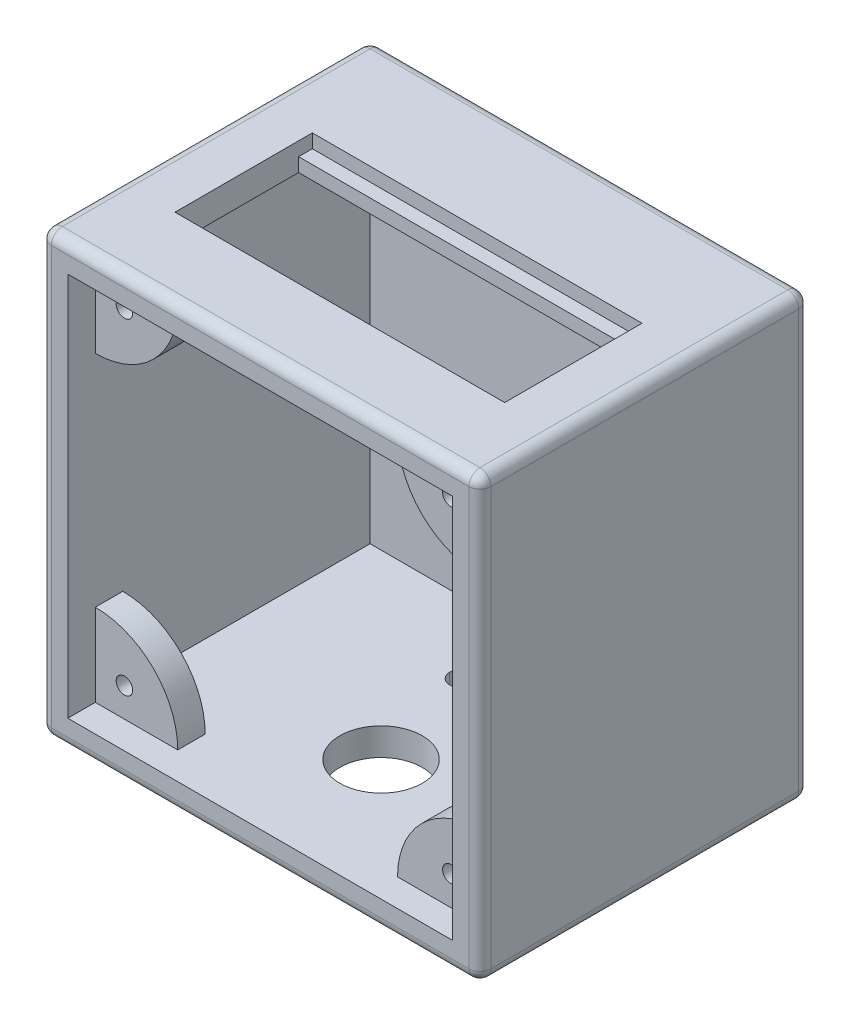
SolidWorks part; units mm, degrees
ref_plane "Спереди" through (0, 0, 0) normal (0, 0, 1) x (1, 0, 0)
ref_plane "Сверху" through (0, 0, 0) normal (0, 1, 0) x (1, 0, 0)
ref_plane "Справа" through (0, 0, 0) normal (1, 0, 0) x (0, 0, -1)
other "Configuration Table"
sketch "Эскиз1" plane through (0, 0, 0) normal (0, 0, 1) x (1, 0, 0)
  line L1 (40, -40) -> (-40, -40)
  line L2 (40, -40) -> (40, 40)
  line L3 (40, 40) -> (-40, 40)
  line L4 (-40, -40) -> (-40, 40)
  line L5 (40, -40) -> (-40, 40) construction
  line L6 (40, 40) -> (-40, -40) construction
  line L11 (35, -35) -> (-35, 35) construction
  line L12 (35, 35) -> (-35, -35) construction
  point P0 (0, 0)
  point P6 (0, 0)
  dimension "D1" = 80
  dimension "D2" = 80
extrude "Бобышка-Вытянуть2" add sketch "Эскиз1" along normal blind 60
sketch "Эскиз2" plane through (0, 0, 60) normal (0, 0, 1) x (1, 0, 0)
  line L0 (-40, 40) -> (-40, -40) construction
  line L1 (35, -35) -> (-35, -35)
  line L2 (35, -35) -> (35, 35)
  line L3 (35, 35) -> (-35, 35)
  line L4 (-35, -35) -> (-35, 35)
  line L5 (35, -35) -> (-35, 35) construction
  line L6 (35, 35) -> (-35, -35) construction
  line L7 (-40, -40) -> (40, -40) construction
  point P0 (0, 0)
  dimension "D1" = 5
  dimension "D2" = 5
extrude "Вырез-Вытянуть1" cut sketch "Эскиз2" against normal blind 55
sketch "Эскиз3" plane through (0, 0, 60) normal (0, 0, 1) x (1, 0, 0)
  line L0 (-35, 35) -> (-35, -35) construction
  line L3 (35, 35) -> (-35, 35) construction
  line L4 (-35, 35) -> (-35, -35) construction
  line L5 (-35, -35) -> (35, -35) construction
  line L6 (-35, -35) -> (35, -35) construction
  line L7 (35, -35) -> (35, 35) construction
  line L8 (-35, 35) -> (-35, 20)
  line L9 (-20, 35) -> (-35, 35)
  line L10 (35, 35) -> (35, 20)
  line L11 (20, 35) -> (35, 35)
  line L12 (20, -35) -> (35, -35)
  line L13 (35, -35) -> (35, -20)
  line L14 (-35, -20) -> (-35, -35)
  line L15 (-35, -35) -> (-20, -35)
  arc A0 (-35, 20) -> (-20, 35) centre (-35, 35) ccw
  arc A1 (20, 35) -> (35, 20) centre (35, 35) ccw
  arc A2 (-35, -20) -> (-20, -35) centre (-35, -35) cw
  arc A3 (20, -35) -> (35, -20) centre (35, -35) cw
  dimension "D1" = 15
  dimension "D2" = 15
  dimension "D3" = 15
  dimension "D4" = 15
extrude "Бобышка-Вытянуть3" add sketch "Эскиз3" against normal blind 10 separate body contours L13 A3 L12 | L9 L8 A0 | L11 L10 A1 | L15 A2 L14
sketch "Эскиз5" plane through (0, 0, 60) normal (0, 0, 1) x (1, 0, 0)
  line L0 (-35, 35) -> (-20, 35)
  line L1 (-35, 20) -> (-35, 35)
  line L2 (35, 35) -> (35, 20)
  line L3 (20, 35) -> (35, 35)
  line L4 (35, -20) -> (35, -35)
  line L5 (35, -35) -> (20, -35)
  line L6 (-20, -35) -> (-35, -35)
  line L7 (-35, -35) -> (-35, -20)
  arc A0 (-35, 20) -> (-20, 35) centre (-35, 35) ccw
  arc A1 (20, 35) -> (35, 20) centre (35, 35) ccw
  arc A2 (35, -20) -> (20, -35) centre (35, -35) ccw
  arc A3 (-20, -35) -> (-35, -20) centre (-35, -35) ccw
extrude "Вырез-Вытянуть2" cut sketch "Эскиз5" against normal blind 5
sketch "Эскиз6" plane through (0, 0, 55) normal (0, 0, 1) x (1, 0, 0)
  line L0 (-35, 35) -> (-24.3934, 24.3934) construction
  line L1 (35, 35) -> (24.3934, 24.3934) construction
  line L3 (-40, 0) -> (40, 0) construction
  line L4 (-40, 40) -> (-40, -40) construction
  line L5 (40, -40) -> (40, 40) construction
  arc A0 (-35, 20) -> (-20, 35) centre (-35, 35) ccw construction
  circle A1 centre (-29.6967, 29.6967) radius 1.5
  arc A2 (20, 35) -> (35, 20) centre (35, 35) ccw construction
  circle A3 centre (29.6967, 29.6967) radius 1.5
  circle A4 centre (29.6967, -29.6967) radius 1.5
  circle A5 centre (-29.6967, -29.6967) radius 1.5
  dimension "D1" = 3
  dimension "D2" = 3
extrude "Вырез-Вытянуть3" cut sketch "Эскиз6" against normal blind 5
sketch "Эскиз7" plane through (0, -40, 0) normal (0, -1, 0) x (1, 0, 0)
  line L0 (0, 60) -> (0, 0) construction
  line L1 (-40, 60) -> (40, 60) construction
  line L2 (-40, 0) -> (40, 0) construction
  line L3 (-40, 60) -> (-40, 0) construction
  line L4 (40, 5) -> (-40, 5) construction
  line L5 (40, 60) -> (40, 0) construction
  line L6 (-40, 10) -> (42.1215, 10) construction
  line L7 (40, 10) -> (42.1215, 10) construction
  line L13 (5.5, 20) -> (-5.5, 20)
  line L14 (7.5, 18) -> (7.5, 12)
  line L15 (5.5, 10) -> (-5.5, 10)
  line L16 (-7.5, 18) -> (-7.5, 12)
  line L17 (7.5, 20) -> (-7.5, 10) construction
  line L18 (7.5, 10) -> (-7.5, 20) construction
  arc A4 (5.5, 20) -> (7.5, 18) centre (5.5, 18) cw
  arc A5 (7.5, 12) -> (5.5, 10) centre (5.5, 12) cw
  arc A6 (-5.5, 10) -> (-7.5, 12) centre (-5.5, 12) cw
  arc A7 (-5.5, 20) -> (-7.5, 18) centre (-5.5, 18) ccw
  point P16 (0, 15)
  dimension "D5" = 2
  dimension "D1" = 5
  dimension "D2" = 5
  dimension "D3" = 15
  dimension "D4" = 10
extrude "Вырез-Вытянуть4" cut sketch "Эскиз7" against normal blind 5
fillet "Скругление1" radius 2 2 edges at (40, -40, 30) (-40, -40, 30)
fillet "Скругление2" radius 2 2 edges at (-40, 40, 30) (40, 40, 30)
fillet "Скругление3" radius 2 8 edges at (39.4142, 39.4142, 60) (39.4142, -39.4142, 60) (-39.4142, -39.4142, 60) (-39.4142, 39.4142, 60) (0, -40, 60) (-40, 0, 60) (40, 0, 60) (0, 40, 60)
fillet "Скругление4" radius 2 8 edges at (-39.4142, -39.4142, 0) (-39.4142, 39.4142, 0) (39.4142, 39.4142, 0) (39.4142, -39.4142, 0) (-40, 0, 0) (0, 40, 0) (40, 0, 0) (0, -40, 0)
sketch "Эскиз10" plane through (0, -40, 0) normal (0, -1, 0) x (1, 0, 0)
  line L0 (0, 58) -> (0, 0) construction
  line L1 (38, 58) -> (-38, 58) construction
  line L2 (38, 0) -> (-38, 0) construction
  circle A0 centre (0, 38) radius 7.5
  dimension "D1" = 15
  dimension "D2" = 20
extrude "Вырез-Вытянуть5" cut sketch "Эскиз10" against normal blind 5
sketch "Эскиз11" plane through (0, 40, 0) normal (0, 1, 0) x (1, 0, 0)
  line L0 (0, 0) -> (0, -58) construction
  line L1 (-38, -58) -> (38, -58) construction
  line L2 (38, -30) -> (-38, -30) construction
  line L3 (38, -58) -> (38, -2) construction
  line L4 (-38, -2) -> (-38, -58) construction
  line L6 (30, -43) -> (-30, -43)
  line L7 (30, -43) -> (30, -23)
  line L8 (30, -23) -> (-30, -23)
  line L9 (-30, -43) -> (-30, -23)
  line L10 (30, -43) -> (-30, -23) construction
  line L11 (30, -23) -> (-30, -43) construction
  point P11 (0, -33)
  dimension "D1" = 15
  dimension "D2" = 60
  dimension "D3" = 20
extrude "Вырез-Вытянуть6" cut sketch "Эскиз11" against normal blind 5
sketch "Эскиз12" plane through (0, 40, 0) normal (0, 1, 0) x (1, 0, 0)
  line L8 (30, -23) -> (-30, -23) construction
  line L10 (30, -23) -> (30, -20.5)
  line L11 (30, -20.5) -> (-30, -20.5)
  line L12 (-30, -23) -> (-30, -20.5)
  line L13 (0, -23) -> (-30, -20.5) construction
  line L14 (30, -20.5) -> (0, -23) construction
  line L15 (-30, -23) -> (30, -23)
  line L16 (-30, -33) -> (30, -33) construction
  line L17 (-30, -23) -> (-30, -43) construction
  line L18 (30, -43) -> (30, -23) construction
  line L19 (30, -45.5) -> (0, -43) construction
  line L20 (0, -43) -> (-30, -45.5) construction
  line L21 (-30, -43) -> (30, -43)
  line L22 (-30, -43) -> (-30, -45.5)
  line L23 (30, -45.5) -> (-30, -45.5)
  line L24 (30, -43) -> (30, -45.5)
  point P0 (0, -23)
  point P23 (0, -43)
  dimension "D1" = 60
  dimension "D2" = 2.5
extrude "Вырез-Вытянуть9" cut sketch "Эскиз12" against normal blind 2.5 contours L10 L11 L12 L15 | L21 L24 L23 L22
